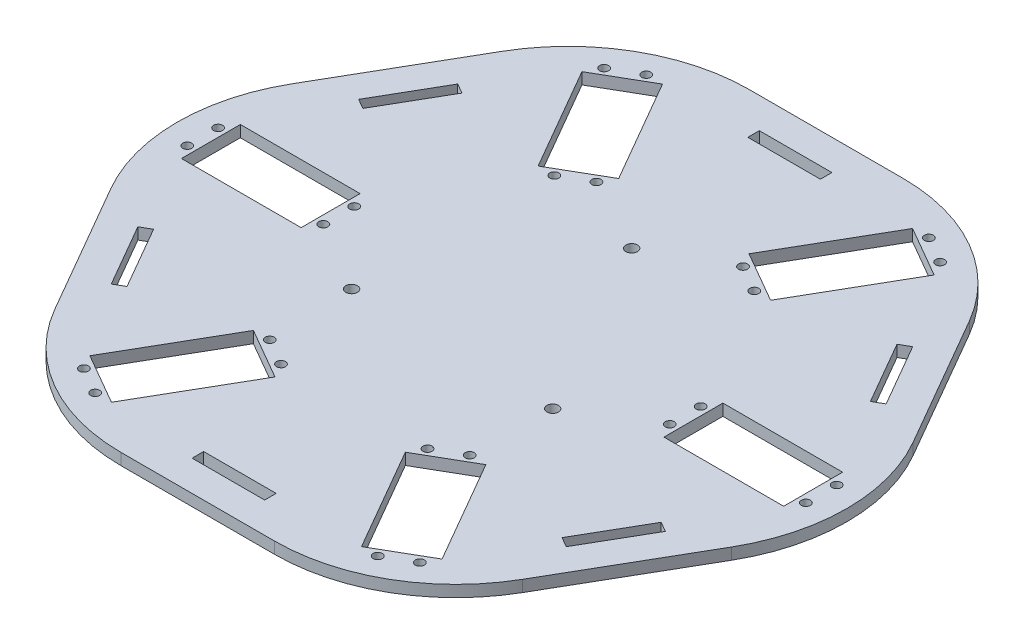
SolidWorks part; units mm, degrees
material "Acrylic (Medium-high impact)"
ref_plane "Front Plane" through (0, 0, 0) normal (0, 0, 1) x (1, 0, 0)
ref_plane "Top Plane" through (0, 0, 0) normal (0, 1, 0) x (1, 0, 0)
ref_plane "Right Plane" through (0, 0, 0) normal (1, 0, 0) x (0, 0, -1)
sketch "Sketch1" plane through (0, 0, 0) normal (0, 1, 0) x (1, 0, 0)
  line L0 (0, 0) -> (200, 0)
  line L1 (171.1325, 50) -> (128.8675, 123.2051)
  line L2 (42.265, 173.2051) -> (-42.265, 173.2051)
  line L3 (-128.8675, 123.2051) -> (-171.1325, 50)
  line L4 (-171.1325, -50) -> (-128.8675, -123.2051)
  line L5 (-42.265, -173.2051) -> (42.265, -173.2051)
  line L6 (128.8675, -123.2051) -> (171.1325, -50)
  line L7 (100, 16.25) -> (166, 16.25)
  line L8 (100, 16.25) -> (100, -16.25)
  line L9 (166, 16.25) -> (166, -16.25)
  line L10 (100, -16.25) -> (166, -16.25)
  line L11 (0, -55) -> (0, 55) construction
  line L12 (-55, 0) -> (55, 0) construction
  line L13 (64.0729, -78.4775) -> (97.0729, -135.6352)
  line L14 (64.0729, -78.4775) -> (35.9271, -94.7275)
  line L15 (35.9271, -94.7275) -> (68.9271, -151.8852)
  line L16 (97.0729, -135.6352) -> (68.9271, -151.8852)
  line L17 (-35.9271, -94.7275) -> (-68.9271, -151.8852)
  line L18 (-35.9271, -94.7275) -> (-64.0729, -78.4775)
  line L19 (-64.0729, -78.4775) -> (-97.0729, -135.6352)
  line L20 (-68.9271, -151.8852) -> (-97.0729, -135.6352)
  line L21 (-100, -16.25) -> (-166, -16.25)
  line L22 (-100, -16.25) -> (-100, 16.25)
  line L23 (-100, 16.25) -> (-166, 16.25)
  line L24 (-166, -16.25) -> (-166, 16.25)
  line L25 (-64.0729, 78.4775) -> (-97.0729, 135.6352)
  line L26 (-64.0729, 78.4775) -> (-35.9271, 94.7275)
  line L27 (-35.9271, 94.7275) -> (-68.9271, 151.8852)
  line L28 (-97.0729, 135.6352) -> (-68.9271, 151.8852)
  line L29 (35.9271, 94.7275) -> (68.9271, 151.8852)
  line L30 (35.9271, 94.7275) -> (64.0729, 78.4775)
  line L31 (64.0729, 78.4775) -> (97.0729, 135.6352)
  line L32 (68.9271, 151.8852) -> (97.0729, 135.6352)
  line L33 (-139.9038, -57.6795) -> (-145.4031, -60.8545)
  line L34 (-20, -150) -> (20, -150)
  line L35 (-20, -150) -> (-20, -156.35)
  line L36 (-20, -156.35) -> (20, -156.35)
  line L37 (20, -150) -> (20, -156.35)
  line L38 (-139.9038, -57.6795) -> (-119.9038, -92.3205)
  line L39 (-119.9038, -92.3205) -> (-125.4031, -95.4955)
  line L40 (-145.4031, -60.8545) -> (-125.4031, -95.4955)
  line L41 (-119.9038, 92.3205) -> (-125.4031, 95.4955)
  line L42 (-119.9038, 92.3205) -> (-139.9038, 57.6795)
  line L43 (-139.9038, 57.6795) -> (-145.4031, 60.8545)
  line L44 (-125.4031, 95.4955) -> (-145.4031, 60.8545)
  line L45 (20, 150) -> (20, 156.35)
  line L46 (20, 150) -> (-20, 150)
  line L47 (-20, 150) -> (-20, 156.35)
  line L48 (20, 156.35) -> (-20, 156.35)
  line L49 (139.9038, 57.6795) -> (145.4031, 60.8545)
  line L50 (139.9038, 57.6795) -> (119.9038, 92.3205)
  line L51 (119.9038, 92.3205) -> (125.4031, 95.4955)
  line L52 (145.4031, 60.8545) -> (125.4031, 95.4955)
  line L53 (119.9038, -92.3205) -> (125.4031, -95.4955)
  line L54 (119.9038, -92.3205) -> (139.9038, -57.6795)
  line L55 (139.9038, -57.6795) -> (145.4031, -60.8545)
  line L56 (125.4031, -95.4955) -> (145.4031, -60.8545)
  line L57 (68.9271, -151.8852) -> (71.9582, -150.1352)
  line L58 (166, 16.25) -> (153, 16.25)
  line L59 (166, 16.25) -> (166, 12.75)
  line L60 (166, 12.75) -> (153, 12.75)
  line L61 (153, 16.25) -> (153, 12.75)
  line L62 (100, -16.25) -> (113, -16.25)
  line L63 (100, -16.25) -> (100, -12.75)
  line L64 (100, -12.75) -> (113, -12.75)
  line L65 (113, -16.25) -> (113, -12.75)
  line L66 (166, -16.25) -> (153, -16.25)
  line L67 (166, -16.25) -> (166, -12.75)
  line L68 (166, -12.75) -> (153, -12.75)
  line L69 (153, -16.25) -> (153, -12.75)
  line L70 (100, 16.25) -> (113, 16.25)
  line L71 (100, 16.25) -> (100, 12.75)
  line L72 (100, 12.75) -> (113, 12.75)
  line L73 (113, 16.25) -> (113, 12.75)
  line L74 (68.9271, -151.8852) -> (62.4271, -140.6269)
  line L75 (62.4271, -140.6269) -> (65.4582, -138.8769)
  line L76 (71.9582, -150.1352) -> (65.4582, -138.8769)
  line L77 (97.0729, -135.6352) -> (94.0418, -137.3852)
  line L78 (97.0729, -135.6352) -> (90.5729, -124.3769)
  line L79 (90.5729, -124.3769) -> (87.5418, -126.1269)
  line L80 (94.0418, -137.3852) -> (87.5418, -126.1269)
  line L81 (64.0729, -78.4775) -> (61.0418, -80.2275)
  line L82 (64.0729, -78.4775) -> (70.5729, -89.7359)
  line L83 (70.5729, -89.7359) -> (67.5418, -91.4859)
  line L84 (61.0418, -80.2275) -> (67.5418, -91.4859)
  line L85 (35.9271, -94.7275) -> (38.9582, -92.9775)
  line L86 (35.9271, -94.7275) -> (42.4271, -105.9859)
  line L87 (42.4271, -105.9859) -> (45.4582, -104.2359)
  line L88 (38.9582, -92.9775) -> (45.4582, -104.2359)
  line L89 (-97.0729, -135.6352) -> (-94.0418, -137.3852)
  line L90 (-97.0729, -135.6352) -> (-90.5729, -124.3769)
  line L91 (-90.5729, -124.3769) -> (-87.5418, -126.1269)
  line L92 (-94.0418, -137.3852) -> (-87.5418, -126.1269)
  line L93 (-68.9271, -151.8852) -> (-71.9582, -150.1352)
  line L94 (-68.9271, -151.8852) -> (-62.4271, -140.6269)
  line L95 (-62.4271, -140.6269) -> (-65.4582, -138.8769)
  line L96 (-71.9582, -150.1352) -> (-65.4582, -138.8769)
  line L97 (-35.9271, -94.7275) -> (-38.9582, -92.9775)
  line L98 (-35.9271, -94.7275) -> (-42.4271, -105.9859)
  line L99 (-42.4271, -105.9859) -> (-45.4582, -104.2359)
  line L100 (-38.9582, -92.9775) -> (-45.4582, -104.2359)
  line L101 (-64.0729, -78.4775) -> (-61.0418, -80.2275)
  line L102 (-64.0729, -78.4775) -> (-70.5729, -89.7359)
  line L103 (-70.5729, -89.7359) -> (-67.5418, -91.4859)
  line L104 (-61.0418, -80.2275) -> (-67.5418, -91.4859)
  line L105 (-166, 16.25) -> (-166, 12.75)
  line L106 (-166, 16.25) -> (-153, 16.25)
  line L107 (-153, 16.25) -> (-153, 12.75)
  line L108 (-166, 12.75) -> (-153, 12.75)
  line L109 (-166, -16.25) -> (-166, -12.75)
  line L110 (-166, -16.25) -> (-153, -16.25)
  line L111 (-153, -16.25) -> (-153, -12.75)
  line L112 (-166, -12.75) -> (-153, -12.75)
  line L113 (-100, -16.25) -> (-100, -12.75)
  line L114 (-100, -16.25) -> (-113, -16.25)
  line L115 (-113, -16.25) -> (-113, -12.75)
  line L116 (-100, -12.75) -> (-113, -12.75)
  line L117 (-100, 16.25) -> (-100, 12.75)
  line L118 (-100, 16.25) -> (-113, 16.25)
  line L119 (-113, 16.25) -> (-113, 12.75)
  line L120 (-100, 12.75) -> (-113, 12.75)
  line L121 (-68.9271, 151.8852) -> (-71.9582, 150.1352)
  line L122 (-68.9271, 151.8852) -> (-62.4271, 140.6269)
  line L123 (-62.4271, 140.6269) -> (-65.4582, 138.8769)
  line L124 (-71.9582, 150.1352) -> (-65.4582, 138.8769)
  line L125 (-97.0729, 135.6352) -> (-94.0418, 137.3852)
  line L126 (-97.0729, 135.6352) -> (-90.5729, 124.3769)
  line L127 (-90.5729, 124.3769) -> (-87.5418, 126.1269)
  line L128 (-94.0418, 137.3852) -> (-87.5418, 126.1269)
  line L129 (-64.0729, 78.4775) -> (-61.0418, 80.2275)
  line L130 (-64.0729, 78.4775) -> (-70.5729, 89.7359)
  line L131 (-70.5729, 89.7359) -> (-67.5418, 91.4859)
  line L132 (-61.0418, 80.2275) -> (-67.5418, 91.4859)
  line L133 (-35.9271, 94.7275) -> (-38.9582, 92.9775)
  line L134 (-35.9271, 94.7275) -> (-42.4271, 105.9859)
  line L135 (-42.4271, 105.9859) -> (-45.4582, 104.2359)
  line L136 (-38.9582, 92.9775) -> (-45.4582, 104.2359)
  line L137 (97.0729, 135.6352) -> (94.0418, 137.3852)
  line L138 (97.0729, 135.6352) -> (90.5729, 124.3769)
  line L139 (90.5729, 124.3769) -> (87.5418, 126.1269)
  line L140 (94.0418, 137.3852) -> (87.5418, 126.1269)
  line L141 (68.9271, 151.8852) -> (71.9582, 150.1352)
  line L142 (68.9271, 151.8852) -> (62.4271, 140.6269)
  line L143 (62.4271, 140.6269) -> (65.4582, 138.8769)
  line L144 (71.9582, 150.1352) -> (65.4582, 138.8769)
  line L145 (35.9271, 94.7275) -> (38.9582, 92.9775)
  line L146 (35.9271, 94.7275) -> (42.4271, 105.9859)
  line L147 (42.4271, 105.9859) -> (45.4582, 104.2359)
  line L148 (38.9582, 92.9775) -> (45.4582, 104.2359)
  line L149 (64.0729, 78.4775) -> (61.0418, 80.2275)
  line L150 (64.0729, 78.4775) -> (70.5729, 89.7359)
  line L151 (70.5729, 89.7359) -> (67.5418, 91.4859)
  line L152 (61.0418, 80.2275) -> (67.5418, 91.4859)
  circle A0 centre (0, 0) radius 200 construction
  circle A5 centre (40.3888, -86.9554) radius 2.5
  circle A6 centre (55.1112, -78.4554) radius 2.5
  circle A7 centre (92.6112, -143.4073) radius 2.5
  circle A8 centre (77.8888, -151.9073) radius 2.5
  circle A9 centre (-55.1112, -78.4554) radius 2.5
  circle A10 centre (-40.3888, -86.9554) radius 2.5
  circle A11 centre (-77.8888, -151.9073) radius 2.5
  circle A12 centre (-92.6112, -143.4073) radius 2.5
  circle A13 centre (-95.5, 8.5) radius 2.5
  circle A14 centre (-95.5, -8.5) radius 2.5
  circle A15 centre (-170.5, -8.5) radius 2.5
  circle A16 centre (-170.5, 8.5) radius 2.5
  circle A17 centre (-40.3888, 86.9554) radius 2.5
  circle A18 centre (-55.1112, 78.4554) radius 2.5
  circle A19 centre (-92.6112, 143.4073) radius 2.5
  circle A20 centre (-77.8888, 151.9073) radius 2.5
  circle A21 centre (55.1112, 78.4554) radius 2.5
  circle A22 centre (40.3888, 86.9554) radius 2.5
  circle A23 centre (77.8888, 151.9073) radius 2.5
  circle A24 centre (92.6112, 143.4073) radius 2.5
  arc A25 (-42.265, 173.2051) -> (-128.8675, 123.2051) centre (-42.265, 73.2051) ccw
  arc A26 (-171.1325, 50) -> (-171.1325, -50) centre (-84.5299, 0) ccw
  arc A27 (-128.8675, -123.2051) -> (-42.265, -173.2051) centre (-42.265, -73.2051) ccw
  arc A28 (42.265, -173.2051) -> (128.8675, -123.2051) centre (42.265, -73.2051) ccw
  arc A29 (171.1325, -50) -> (171.1325, 50) centre (84.5299, 0) ccw
  arc A30 (128.8675, 123.2051) -> (42.265, 173.2051) centre (42.265, 73.2051) ccw
  circle A31 centre (95.5, 8.5) radius 2.5
  circle A32 centre (95.5, -8.5) radius 2.5
  circle A33 centre (170.5, -8.5) radius 2.5
  circle A34 centre (170.5, 8.5) radius 2.5
  point P88 (0, 0)
  point P94 (100, -173.2051)
  point P102 (0, 0)
  point P128 (0, 0)
  point P220 (0, 0)
  dimension "D1" = 400
  dimension "D7" = 2
  dimension "D8" = 40
  dimension "D9" = 20
  dimension "D10" = 6.35
  dimension "D20" = 100
  dimension "D2" = 200
  dimension "D3" = 66
  dimension "D4" = 32.5
  dimension "D5" = 100
  dimension "D6" = 16.25
  dimension "D11" = 150
  dimension "D12" = 6
  dimension "D13" = 13
  dimension "D14" = 3.5
  dimension "D15" = 13
  dimension "D16" = 3.5
  dimension "D17" = 6
  dimension "D19" = 6
extrude "Boss-Extrude1" add sketch "Sketch1" along normal blind 6.35
sketch "Sketch2" plane through (0, 6.35, 0) normal (0, 1, 0) x (1, 0, 0)
  line L0 (0, -1.1339) -> (85.0289, -1.1339)
  line L1 (0, -55) -> (0, 55) construction
  line L2 (55.7942, -33.3467) -> (0, -1.1339)
  circle A0 centre (55.7942, -33.3467) radius 3.2
  circle A1 centre (-56.7762, -31.6459) radius 3.2
  circle A2 centre (0.982, 64.9926) radius 3.2
  point P14 (0, 0)
  dimension "D3" = 6.4
  dimension "D1" = 65
  dimension "D2" = 30
  dimension "D4" = 3
extrude "Cut-Extrude1" cut sketch "Sketch2" against normal up to surface (6.35 mm away) contours A2 | A0 | A1 up to face at (0, 0, 0)
